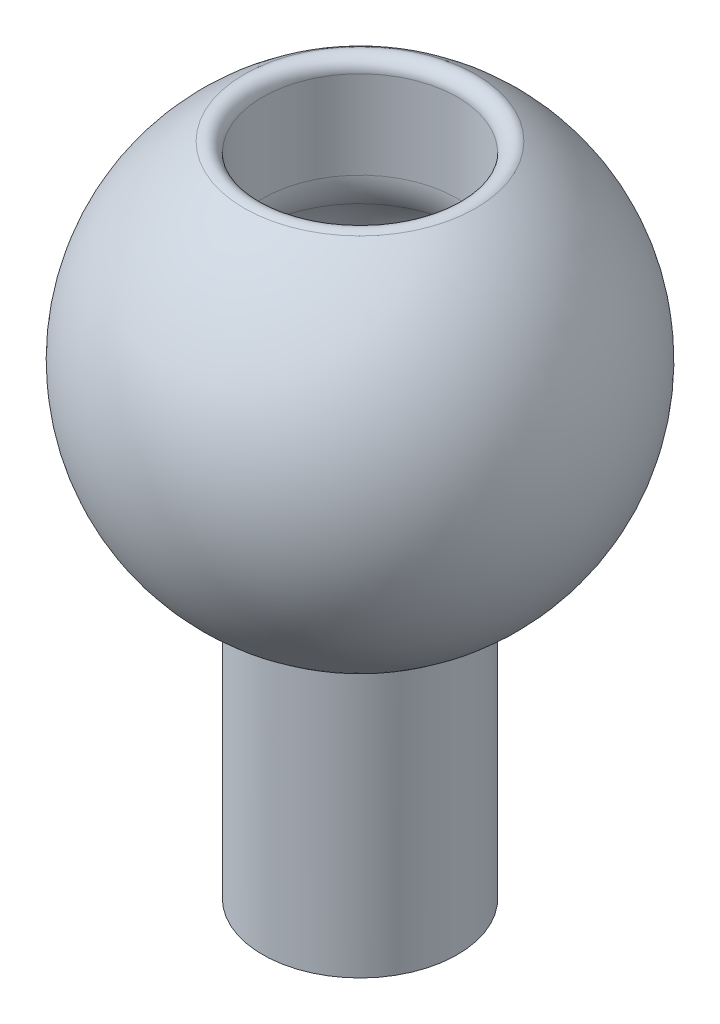
SolidWorks part; units mm, degrees
material "201 Annealed Stainless Steel (SS)"
ref_plane "Front Plane" through (0, 0, 0) normal (0, 0, 1) x (1, 0, 0)
ref_plane "Top Plane" through (0, 0, 0) normal (0, 1, 0) x (1, 0, 0)
ref_plane "Right Plane" through (0, 0, 0) normal (1, 0, 0) x (0, 0, -1)
sketch "Sketch1" plane through (0, 0, 0) normal (0, 1, 0) x (1, 0, 0)
  line L0 (-10, 0) -> (10, 0)
  line L1 (-18.2327, 0) -> (-10, 0)
  line L2 (10, 0) -> (18.2327, 0)
  arc A0 (-10, 0) -> (10, 0) centre (0, 0) ccw
  arc A1 (-18.2327, 0) -> (18.2327, 0) centre (0, 0) ccw
revolve "Revolve1" add sketch "Sketch1" angle 360 about L0
ref_plane "Plane1" through (0, 18.2327, 0) normal (0, 1, 0) x (1, 0, 0)
sketch "Sketch2" plane through (0, 18.2327, 0) normal (0, 1, 0) x (1, 0, 0)
  circle A0 centre (0, 0) radius 8
extrude "Cut-Extrude1" cut sketch "Sketch2" against normal blind 16 contours A0
fillet "Fillet2" radius 5 1 edges at (0, 6, -8)
fillet "Fillet3" radius 1 1 edges at (0, 16.3839, -8)
ref_plane "Plane2" through (0, -18.2327, 0) normal (0, -1, 0) x (-1, 0, 0)
sketch "Sketch3" plane through (0, -18.2327, 0) normal (0, -1, 0) x (-1, 0, 0)
  circle A0 centre (0, 0) radius 8 construction
  circle A1 centre (0, 0) radius 8
extrude "Boss-Extrude1" add sketch "Sketch3" along normal blind 20.085 and the other way blind 3
